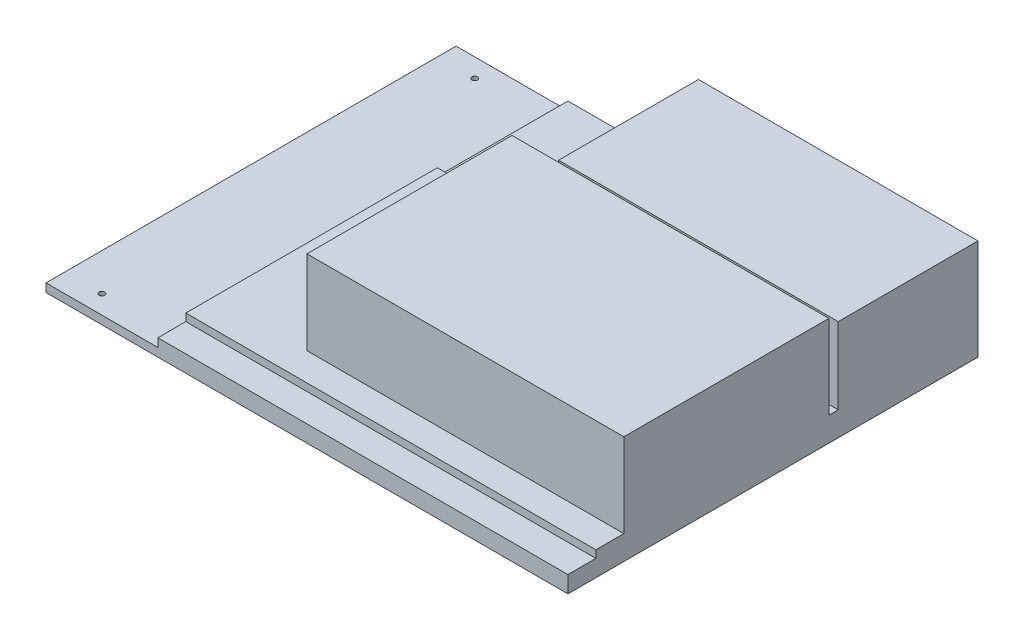
SolidWorks part; units mm, degrees
material "Perspex (TM) GS Acrylic Cast Sheet"
ref_plane "Front Plane" through (0, 0, 0) normal (0, 0, 1) x (1, 0, 0)
ref_plane "Top Plane" through (0, 0, 0) normal (0, 1, 0) x (1, 0, 0)
ref_plane "Right Plane" through (0, 0, 0) normal (1, 0, 0) x (0, 0, -1)
sketch "Sketch1" plane through (0, 0, 0) normal (0, 1, 0) x (1, 0, 0)
  line L1 (-128.3019, 71.5094) -> (91.6981, 71.5094)
  line L2 (-128.3019, 71.5094) -> (-128.3019, -148.4906)
  line L3 (-128.3019, -148.4906) -> (91.6981, -148.4906)
  line L4 (91.6981, 71.5094) -> (91.6981, -148.4906)
  dimension "D1" = 220
  dimension "D2" = 220
extrude "Boss-Extrude1" add sketch "Sketch1" along normal blind 4.5
sketch "Sketch2" plane through (0, 4.5, 0) normal (0, 1, 0) x (1, 0, 0)
  line L0 (-128.3019, -133.4906) -> (91.6981, -133.4906)
  line L1 (-128.3019, 71.5094) -> (-128.3019, -148.4906) construction
  line L2 (91.6981, -148.4906) -> (91.6981, 71.5094) construction
  line L3 (91.6981, -133.4906) -> (91.6981, 1.5094)
  line L4 (91.6981, 1.5094) -> (-128.3019, 1.5094)
  line L5 (-128.3019, 1.5094) -> (-128.3019, -133.4906)
  line L6 (-128.3019, -148.4906) -> (91.6981, -148.4906) construction
  dimension "D1" = 15
  dimension "D2" = 150
extrude "Boss-Extrude2" add sketch "Sketch2" along normal blind 4
sketch "Sketch3" plane through (0, 4.5, 0) normal (0, 1, 0) x (1, 0, 0)
  line L0 (91.6981, 1.5094) -> (91.6981, 71.5094) construction
  line L1 (-58.3019, 71.5094) -> (91.6981, 71.5094)
  line L2 (-58.3019, 71.5094) -> (-58.3019, -3.4906)
  line L3 (-58.3019, -3.4906) -> (91.6981, -3.4906)
  line L4 (91.6981, 71.5094) -> (91.6981, -3.4906)
  line L5 (91.6981, 71.5094) -> (-128.3019, 71.5094) construction
  dimension "D1" = 150
  dimension "D2" = 75
extrude "Boss-Extrude3" add sketch "Sketch3" along normal blind 45
sketch "Sketch4" plane through (0, 8.5, 0) normal (0, 1, 0) x (1, 0, 0)
  line L0 (91.6981, -133.4906) -> (91.6981, -3.4906) construction
  line L1 (-78.3019, -8.4906) -> (91.6981, -8.4906)
  line L2 (-78.3019, -8.4906) -> (-78.3019, -118.4906)
  line L3 (-78.3019, -118.4906) -> (91.6981, -118.4906)
  line L4 (91.6981, -8.4906) -> (91.6981, -118.4906)
  line L5 (-128.3019, -148.4906) -> (91.6981, -148.4906) construction
  dimension "D1" = 170
  dimension "D2" = 140
  dimension "D3" = 110
extrude "Boss-Extrude4" add sketch "Sketch4" along normal blind 45
sketch "Sketch5" plane through (0, 0, 0) normal (0, -1, 0) x (1, 0, 0)
  line L0 (91.6981, -71.5094) -> (-128.3019, -71.5094) construction
  line L1 (91.6981, 148.4906) -> (-188.3019, 148.4906)
  line L2 (91.6981, 148.4906) -> (91.6981, -71.5094)
  line L3 (91.6981, -71.5094) -> (-188.3019, -71.5094)
  line L4 (-188.3019, 148.4906) -> (-188.3019, -71.5094)
  line L5 (-128.3019, -71.5094) -> (-128.3019, 148.4906) construction
  dimension "D1" = 60
extrude "Boss-Extrude5" add sketch "Sketch5" along normal blind 4.5 contours L4 L3 L2 L1
sketch "Sketch6" plane through (0, 0, 0) normal (0, 1, 0) x (1, 0, 0)
  line L0 (-128.3019, 71.5094) -> (-188.3019, 71.5094) construction
  line L1 (-188.3019, -148.4906) -> (-188.3019, 71.5094) construction
  line L2 (-128.3019, -148.4906) -> (-188.3019, -148.4906) construction
  circle A0 centre (-168.3019, 61.5094) radius 1.5
  circle A1 centre (-168.3019, -138.4906) radius 1.5
  dimension "D1" = 3
  dimension "D2" = 10
  dimension "D3" = 20
  dimension "D4" = 10
extrude "Cut-Extrude1" cut sketch "Sketch6" against normal blind 10
